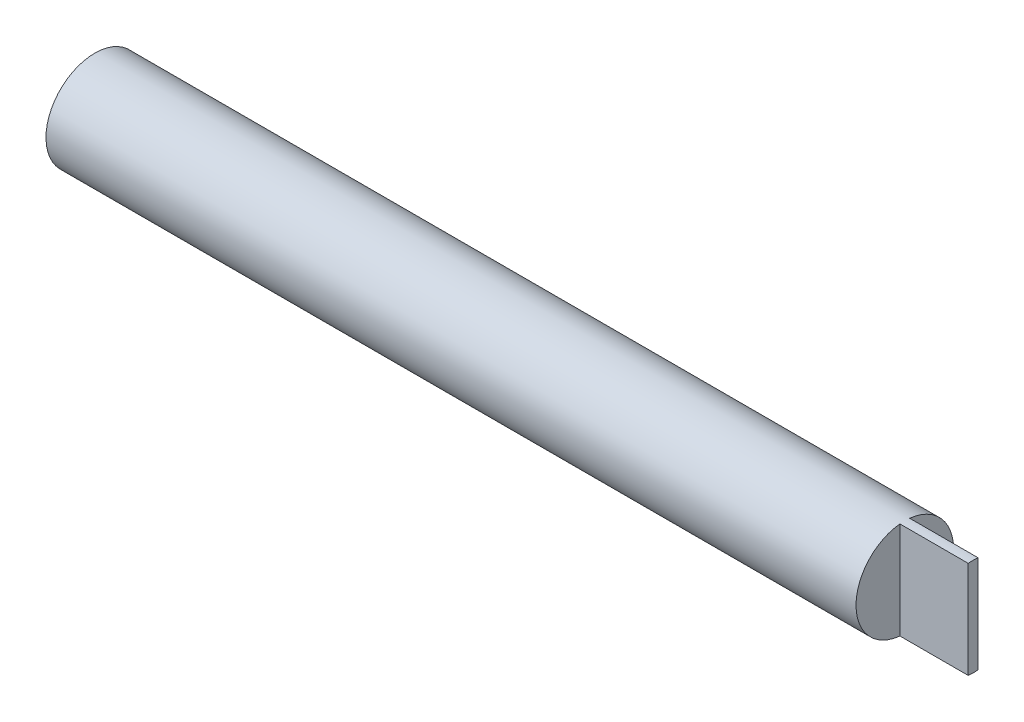
SolidWorks part; units mm, degrees
ref_plane "Front Plane" through (0, 0, 0) normal (0, 0, 1) x (1, 0, 0)
ref_plane "Top Plane" through (0, 0, 0) normal (0, 1, 0) x (1, 0, 0)
ref_plane "Right Plane" through (0, 0, 0) normal (1, 0, 0) x (0, 0, -1)
sketch "Sketch1" plane through (0, 0, 0) normal (1, 0, 0) x (0, 0, -1)
  circle A0 centre (0, 0) radius 5
  dimension "D1" = 10
extrude "Corpo" add sketch "Sketch1" along normal blind 90
sketch "Sketch2" plane through (90, 0, 0) normal (1, 0, 0) x (0, 0, -1)
  line L2 (-0.5, -4.9749) -> (-0.5, 4.9749)
  line L4 (0.5, -4.9749) -> (0.5, 4.9749)
  circle A0 centre (0, 0) radius 5
  circle M4 centre (0, 0) radius 5
  dimension "D1" = 10
  dimension "D2" = 0.5
  dimension "D3" = 0.5
extrude "Aba 1mm" cut sketch "Sketch2" against normal blind 7 contours L2 M4 | L4 M4
